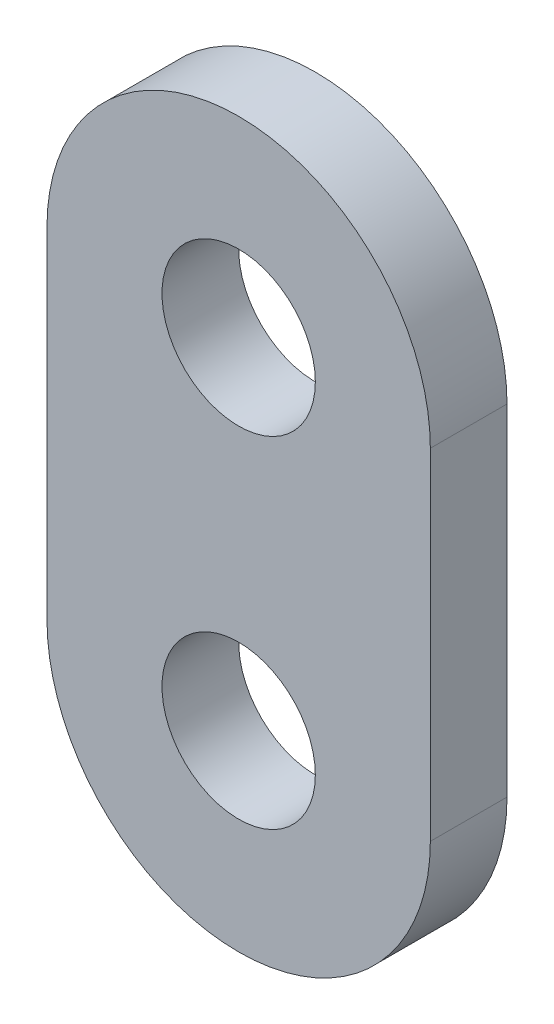
SolidWorks part; units mm, degrees
ref_plane "Alzado" through (0, 0, 0) normal (0, 0, 1) x (1, 0, 0)
ref_plane "Planta" through (0, 0, 0) normal (0, 1, 0) x (1, 0, 0)
ref_plane "Vista lateral" through (0, 0, 0) normal (1, 0, 0) x (0, 0, -1)
sketch "Croquis1" plane through (0, 0, 0) normal (0, 0, 1) x (1, 0, 0)
  line L0 (0, 0) -> (50, 0) construction
  line L1 (50, 0) -> (50, 44.4)
  line L2 (50, 44.4) -> (0, 44.4) construction
  line L3 (0, 44.4) -> (0, 0)
  arc A0 (0, 0) -> (50, 0) centre (25, 0) ccw
  arc A1 (50, 44.4) -> (0, 44.4) centre (25, 44.4) ccw
  circle A2 centre (25, 44.4) radius 10
  circle A3 centre (25, 0) radius 10
  dimension "D3" = 20
  dimension "D4" = 20
  dimension "D1" = 50
  dimension "D2" = 44.4
extrude "Saliente-Extruir1" add sketch "Croquis1" along normal blind 10
